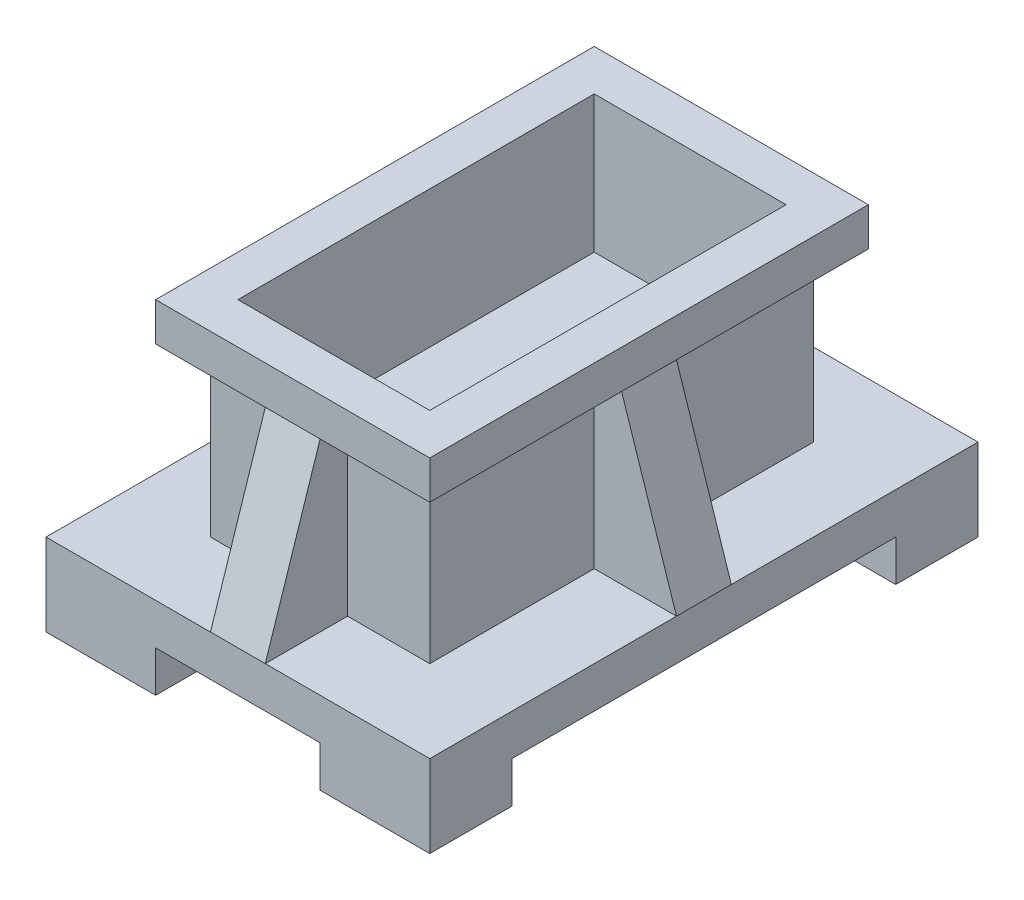
SolidWorks part; units mm, degrees
material "Nickel"
ref_plane "Front Plane" through (0, 0, 0) normal (0, 0, 1) x (1, 0, 0)
ref_plane "Top Plane" through (0, 0, 0) normal (0, 1, 0) x (1, 0, 0)
ref_plane "Right Plane" through (0, 0, 0) normal (1, 0, 0) x (0, 0, -1)
sketch "Sketch1" plane through (0, 0, 0) normal (0, 1, 0) x (1, 0, 0)
  line L1 (70, -100) -> (-70, -100)
  line L2 (70, -100) -> (70, 100)
  line L3 (70, 100) -> (-70, 100)
  line L4 (-70, -100) -> (-70, 100)
  line L5 (70, -100) -> (-70, 100) construction
  line L6 (70, 100) -> (-70, -100) construction
  point P0 (0, 0)
  dimension "D1" = 200
  dimension "D2" = 140
extrude "Boss-Extrude1" add sketch "Sketch1" along normal blind 30
sketch "Sketch2" plane through (70, 0, 0) normal (1, 0, 0) x (0, 0, -1)
  line L0 (-70, 0) -> (-70, 15)
  line L1 (-100, 0) -> (100, 0) construction
  line L2 (-70, 15) -> (70, 15)
  line L3 (70, 15) -> (70, 0)
  line L4 (70, 0) -> (-70, 0)
  line L5 (-100, 30) -> (-100, 0) construction
  line L6 (100, 30) -> (100, 0) construction
  dimension "D1" = 30
  dimension "D2" = 30
  dimension "D3" = 15
extrude "Cut-Extrude1" cut sketch "Sketch2" against normal through all
sketch "Sketch3" plane through (0, 0, 100) normal (0, 0, 1) x (1, 0, 0)
  line L0 (-30, 0) -> (-30, 15)
  line L1 (-30, 15) -> (30, 15)
  line L2 (30, 15) -> (30, 0)
  line L3 (-70, 0) -> (70, 0) construction
  line L4 (30, 0) -> (-30, 0)
  line L5 (-70, 30) -> (-70, 0) construction
  line L6 (70, 30) -> (70, 0) construction
  dimension "D1" = 40
  dimension "D2" = 40
  dimension "D3" = 15
extrude "Cut-Extrude3" cut sketch "Sketch3" against normal through all
sketch "Sketch4" plane through (0, 30, 0) normal (0, 1, 0) x (1, 0, 0)
  line L12 (-40, 70) -> (-40, -70)
  line L13 (-40, -70) -> (40, -70)
  line L14 (40, -70) -> (40, 70)
  line L15 (40, 70) -> (-40, 70)
  line L16 (-40, 70) -> (-40, -70)
  line L17 (-40, -70) -> (40, -70)
  line L18 (40, -70) -> (40, 70)
  line L19 (40, 70) -> (-40, 70)
  dimension "D1" = 30
extrude "Boss-Extrude3" add sketch "Sketch4" along normal blind 61
sketch "Sketch5" plane through (0, 91, 0) normal (0, 1, 0) x (1, 0, 0)
  line L0 (35, 65) -> (-35, 65)
  line L1 (-35, -65) -> (-35, 65)
  line L2 (35, -65) -> (-35, -65)
  line L3 (35, -65) -> (35, 65)
  line L4 (-50, -80) -> (-50, 80)
  line L9 (50, -71.4286) -> (-50, 71.4286) construction
  line L10 (50, 71.4286) -> (-50, -71.4286) construction
  line L11 (50, 80) -> (-50, 80)
  line L12 (50, -80) -> (50, 80)
  line L13 (50, -80) -> (-50, -80)
  point P0 (0, 0)
extrude "Boss-Extrude4" add sketch "Sketch5" along normal blind 14
sketch "Sketch7" plane through (0, 91, 0) normal (0, 1, 0) x (1, 0, 0)
  line L1 (35, -65) -> (-35, -65)
  line L2 (35, -65) -> (35, 65)
  line L3 (35, 65) -> (-35, 65)
  line L4 (-35, -65) -> (-35, 65)
  line L5 (35, -65) -> (-35, 65) construction
  line L6 (35, 65) -> (-35, -65) construction
  point P0 (0, 0)
extrude "Cut-Extrude4" cut sketch "Sketch7" against normal blind 36
sketch "Sketch9" plane through (0, 0, 0) normal (0, 0, 1) x (1, 0, 0)
  line L0 (-50, 91) -> (-70, 30)
  line L1 (-70, 30) -> (-39.9797, 30)
  line L2 (-70, 30) -> (70, 30) construction
  line L3 (-39.9797, 30) -> (-40, 91)
  line L4 (-40, 91) -> (-40, 30) construction
  line L5 (-40, 91) -> (-50, 91)
extrude "Boss-Extrude5" add sketch "Sketch9" along normal blind 10 and the other way blind 10
mirror "Mirror1" about plane through (0, 0, 0) normal (1, 0, 0) of "Boss-Extrude5"
sketch "Sketch10" plane through (0, 0, 0) normal (1, 0, 0) x (0, 0, -1)
  line L0 (-70, 91) -> (-80, 91)
  line L1 (-80, 91) -> (-100, 30)
  line L2 (-100, 30) -> (-70, 30)
  line L3 (-70, 30) -> (-70, 91)
extrude "Boss-Extrude6" add sketch "Sketch10" along normal blind 10 and the other way blind 10
mirror "Mirror2" about plane through (0, 0, 0) normal (0, 0, 1) of "Boss-Extrude6"
